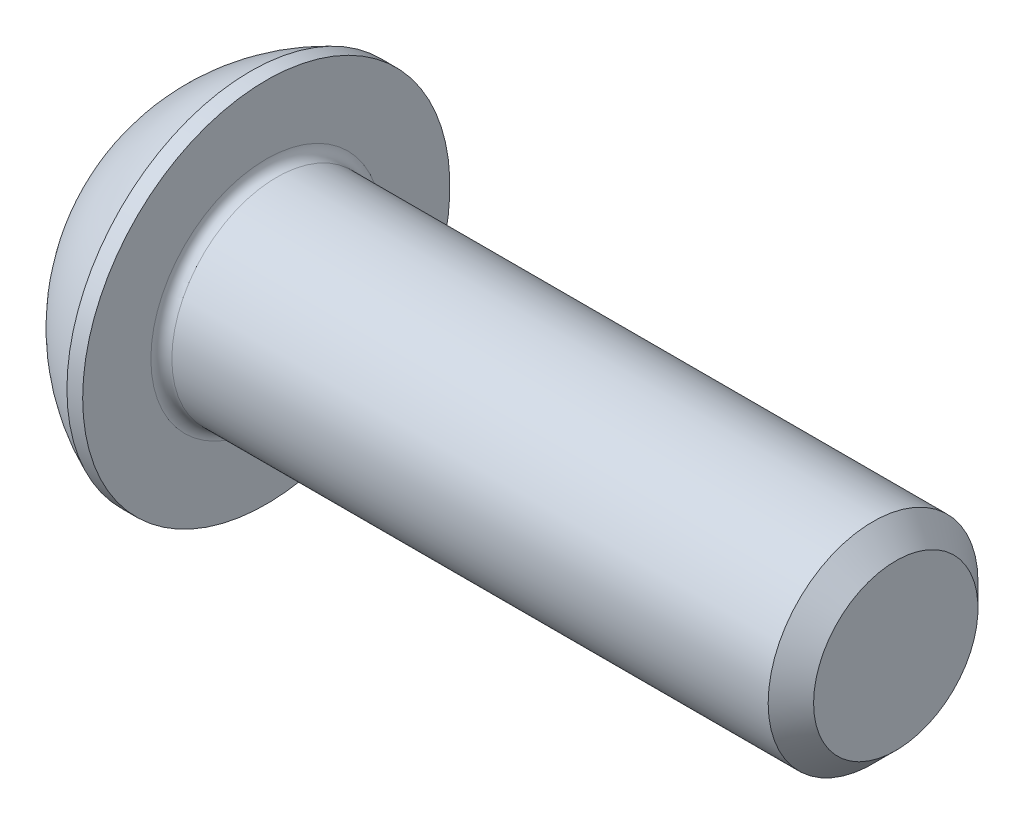
SolidWorks part; units mm, degrees
ref_plane "Plane1" through (0, 0, 0) normal (0, 0, 1) x (1, 0, 0)
ref_plane "Plane2" through (0, 0, 0) normal (0, 1, 0) x (1, 0, 0)
ref_plane "Plane3" through (0, 0, 0) normal (1, 0, 0) x (0, 0, -1)
sketch "BodySke" plane through (0, 0, 0) normal (0, 0, 1) x (1, 0, 0)
  line L0 (7.1, 0) -> (7.1, 0.7835)
  line L1 (6.8835, 1) -> (1.1, 1)
  line L2 (1.1, 1) -> (1.1, 1.75)
  line L3 (1.1, 1.75) -> (0.95, 1.75)
  line L4 (0, 0) -> (101.6, 0) construction
  line L5 (1.1, -1.75) -> (0.95, -1.75) construction
  line L6 (55.6768, -1) -> (1.1, -1) construction
  line L7 (7.1, 0) -> (0, 0)
  line L8 (0, 0.875) -> (0, -0.875) construction
  line L9 (0, 0) -> (0, 0.875)
  line L10 (7.1, 0.7835) -> (6.8835, 1)
  line L11 (7.1, -0.7835) -> (6.8835, -1) construction
  line L12 (1.5, 9.525) -> (1.5, -1) construction
  line L13 (1.1, 9.525) -> (1.1, -1) construction
  arc A1 (0, 0.875) -> (0.95, 1.75) centre (1.6839, 0) cw
  dimension "Diameter" = 2
  dimension "Length" = 6
  dimension "Head_dia" = 3.5
  dimension "D1" = 1.75
  dimension "Head_ht" = 1.1
  dimension "Head_side_ht" = 0.15
  dimension "Minor_dia" = 1.567
  dimension "Body_ch_ang" = 45
  dimension "Advance" = 0.4
  dimension "Thread_nom" = 6
revolve "BaseBody" add sketch "BodySke" angle 360 about L4
cosmetic thread "ThreadCosmetic" [suppressed] parameters "Thread_length"=5.2, "Thread_minor"=1.567
fillet "Fillet1" radius 0.1 1 edges at (1.1, 0, 1)
sketch "Sketch2" plane through (0, 0, 0) normal (0, 0, 1) x (1, 0, 0)
  line L0 (0, 0.715) -> (0.6, 0.715)
  line L1 (0.6, 0.715) -> (1.0128, 0)
  line L3 (1.0128, 0) -> (0, 0)
  line L4 (0, 0) -> (0, 0.715)
  line L5 (0, -0.715) -> (0.6, -0.715) construction
  line L6 (0, 0) -> (47.625, 0) construction
  dimension "D2" = 60
  dimension "PreBroach_depth" = 0.6
  dimension "PreBroach_dia" = 1.43
revolve "PreBroach" cut sketch "Sketch2" angle 360 about L6
sketch "Sketch3" plane through (0, 0, 0) normal (1, 0, 0) x (0, 0, -1)
  line L0 (-0.65, -0.3753) -> (-0.65, 0.3753)
  line L1 (-0.65, 0.3753) -> (0, 0.7506)
  line L2 (0, 0.7506) -> (0.65, 0.3753)
  line L3 (0.65, 0.3753) -> (0.65, -0.3753)
  line L4 (0.65, -0.3753) -> (0, -0.7506)
  line L5 (0, -0.7506) -> (-0.65, -0.3753)
  dimension "Hex_size" = 1.3
  dimension "D3" = 1.3
  dimension "D1" = 0.65
  dimension "D2" = 0.65
extrude "Hex" cut sketch "Sketch3" along normal blind 0.6
sketch "ThdSchSke" plane through (0, 0, 0) normal (0, 0, 1) x (1, 0, 0)
  line L0 (1.9, -0.7835) -> (1.7484, -1)
  line L1 (1.9, -0.7835) -> (2.0516, -1)
  line L2 (2.0516, -1) -> (2.0516, -1.25)
  line L3 (-3.175, 0) -> (5.1513, 0) construction
  line L5 (2.0516, -1.25) -> (1.7484, -1.25)
  line L6 (1.7484, -1.25) -> (1.7484, -1)
  dimension "Diameter" = 2
  dimension "Thread_minor" = 1.567
  dimension "SideAngle" = 55
  dimension "VeeAngle" = 70
  dimension "Overcut" = 2.5
  dimension "Start" = 1.9
revolve "ThreadSchematic" [suppressed] cut sketch "ThdSchSke" angle 360 about L3
pattern_linear "ThdSchPat" [suppressed]
equation "\"D1@BodySke\" = \"Head_dia@BodySke\" * .5"
equation "\"Thread_minor@ThreadCosmetic\" = \"Minor_dia@BodySke\""
equation "\"D1@Sketch3\" = \"Hex_size@Sketch3\" / 2"
equation "\"D2@Sketch3\" = \"D1@Sketch3\""
equation "\"D3@Sketch3\" = \"Hex_size@Sketch3\""
equation "\"Thread_length@ThreadCosmetic\" = ((sgn( (\"Length@BodySke\" - \"Advance@BodySke\" * 2.0) - \"Thread_nom@BodySke\" )-1)*( (\"Length@BodySke\" - \"Advance@BodySke\" * 2.0) - \"Thread_nom@BodySke\" ))/-2+ \"Thread_nom@BodySke\""
equation "\"Thread_minor@ThdSchSke\" = \"Minor_dia@BodySke\""
equation "\"Diameter@ThdSchSke\" = \"Diameter@BodySke\""
equation "\"Overcut@ThdSchSke\" = \"Diameter@BodySke\" * 1.25"
equation "\"Start@ThdSchSke\" = \"Head_ht@BodySke\" + \"Length@BodySke\" - \"Thread_length@ThreadCosmetic\"  '---Non-countersunk---"
equation "\"Num_threads@ThdSchPat\" = int( \"Thread_length@ThreadCosmetic\" / \"Advance@BodySke\" + 0.999 )  + 1"
equation "\"Advance@ThdSchPat\" = \"Thread_length@ThreadCosmetic\" /  (\"Num_threads@ThdSchPat\" - 1) 'relax it"
equation "\"Num_threads@ThdSchPat\" = \"Num_threads@ThdSchPat\" - sgn( \"Num_threads@ThdSchPat\" - 1) '---chamfered tips only---"
